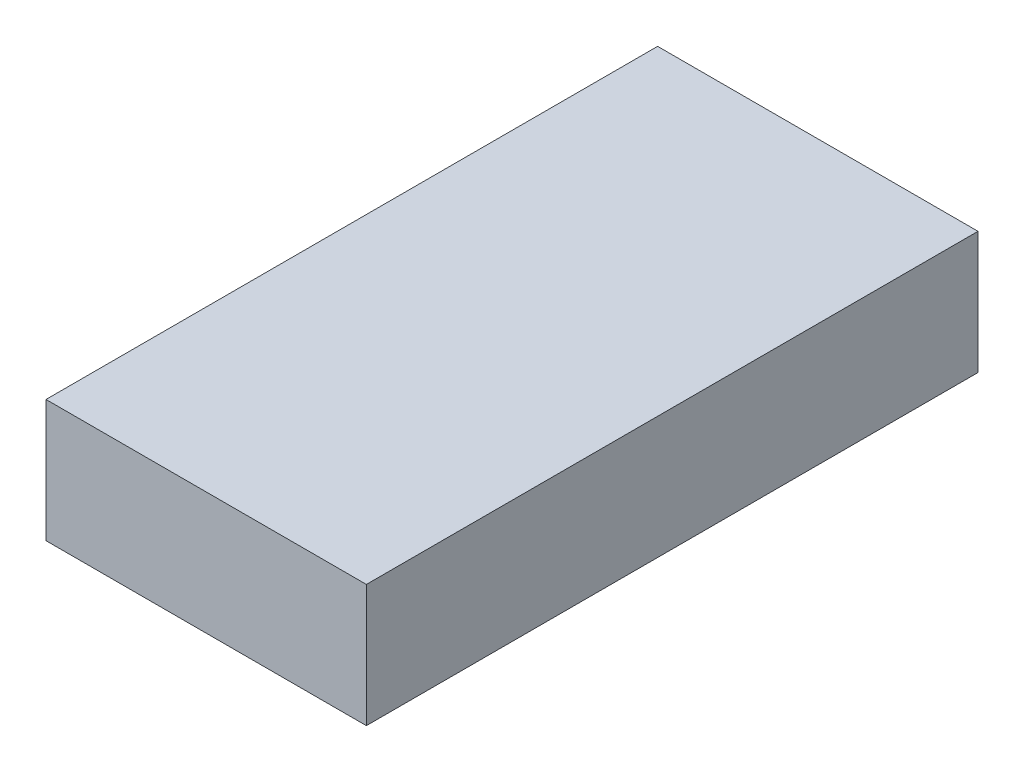
SolidWorks part; units mm, degrees
material "Pololu G2 18v15"
ref_plane "Front Plane" through (0, 0, 0) normal (0, 0, 1) x (1, 0, 0)
ref_plane "Top Plane" through (0, 0, 0) normal (0, 1, 0) x (1, 0, 0)
ref_plane "Right Plane" through (0, 0, 0) normal (1, 0, 0) x (0, 0, -1)
sketch "Sketch1" plane through (0, 0, 0) normal (0, 1, 0) x (1, 0, 0)
  line L1 (-13.97, -26.67) -> (13.97, -26.67)
  line L2 (-13.97, -26.67) -> (-13.97, 26.67)
  line L3 (-13.97, 26.67) -> (13.97, 26.67)
  line L4 (13.97, -26.67) -> (13.97, 26.67)
  line L5 (-13.97, -26.67) -> (13.97, 26.67) construction
  line L6 (-13.97, 26.67) -> (13.97, -26.67) construction
  point P0 (0, 0)
extrude "Boss-Extrude1" add sketch "Sketch1" along normal blind 10.668
